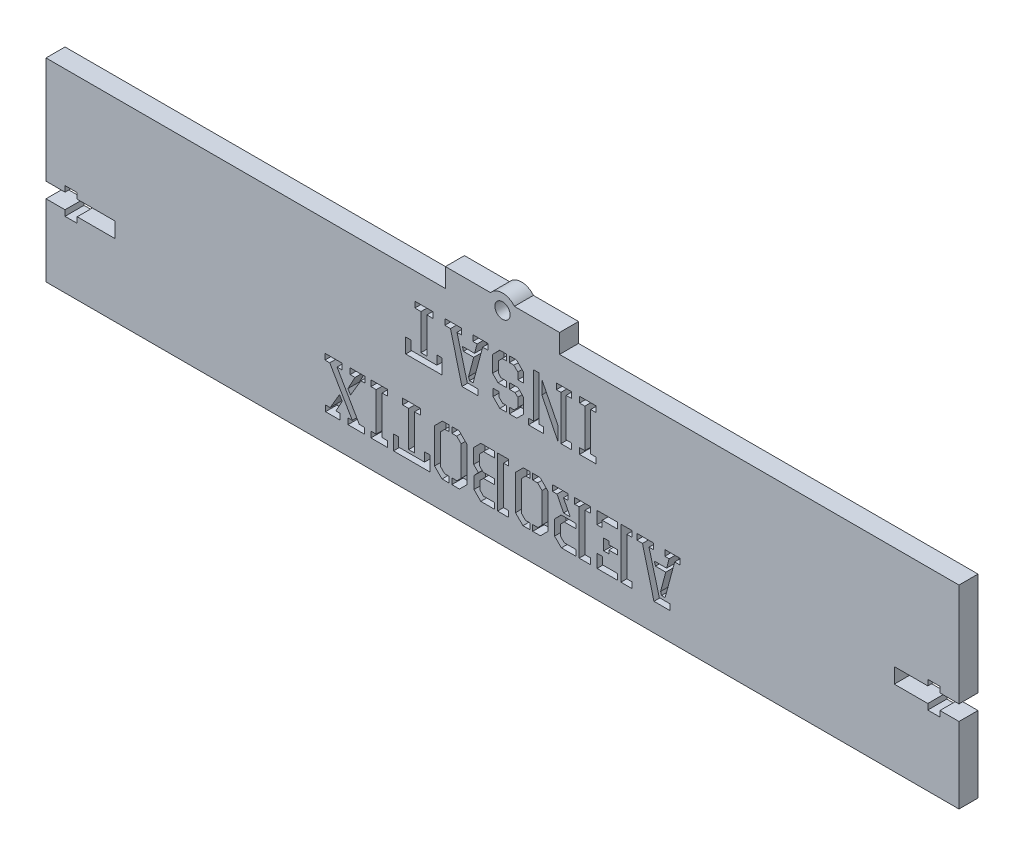
SolidWorks part; units mm, degrees
ref_plane "Front Plane" through (0, 0, 0) normal (0, 0, 1) x (1, 0, 0)
ref_plane "Top Plane" through (0, 0, 0) normal (0, 1, 0) x (1, 0, 0)
ref_plane "Right Plane" through (0, 0, 0) normal (1, 0, 0) x (0, 0, -1)
sketch "Sketch1" plane through (0, 0, 0) normal (0, 0, 1) x (1, 0, 0)
  line L1 (-120, 25.5) -> (120, 25.5)
  line L2 (-120, 25.5) -> (-120, -25.5)
  line L3 (-120, -25.5) -> (120, -25.5)
  line L4 (120, 25.5) -> (120, -25.5)
  dimension "D1" = 240
  dimension "D2" = 51
  dimension "D3" = 25.5
  dimension "D4" = 120
extrude "Boss-Extrude1" add sketch "Sketch1" along normal blind 5
sketch "Sketch4" plane through (0, 0, 5) normal (0, 0, 1) x (1, 0, 0)
  line L0 (120, 25.5) -> (-120, 25.5) construction
  line L1 (-15, 25.5) -> (15, 25.5)
  line L2 (-15, 25.5) -> (-15, 30.5)
  line L3 (-15, 30.5) -> (15, 30.5)
  line L4 (15, 25.5) -> (15, 30.5)
  line L5 (-120, 25.5) -> (-120, -25.5) construction
  dimension "D1" = 105
  dimension "D2" = 30
  dimension "D3" = 5
extrude "Boss-Extrude2" add sketch "Sketch4" against normal blind 5
sketch "Sketch5" plane through (0, 0, 5) normal (0, 0, 1) x (1, 0, 0)
  line L0 (-120, -25.5) -> (120, -25.5) construction
  line L1 (17.5, -25.5) -> (67.5, -25.5)
  line L2 (17.5, -25.5) -> (17.5, -30.5)
  line L3 (17.5, -30.5) -> (67.5, -30.5)
  line L4 (67.5, -25.5) -> (67.5, -30.5)
  line L5 (120, -25.5) -> (120, 25.5) construction
  line L11 (0, 0) -> (0, -46.5213) construction
  line L12 (-67.5, -25.5) -> (-67.5, -30.5)
  line L13 (-17.5, -30.5) -> (-67.5, -30.5)
  line L14 (-17.5, -25.5) -> (-17.5, -30.5)
  line L15 (-17.5, -25.5) -> (-67.5, -25.5)
  point P10 (67.5, -28)
  dimension "D1" = 52.5
  dimension "D2" = 50
  dimension "D3" = 5
extrude "Boss-Extrude3" [suppressed] add sketch "Sketch5" against normal blind 5
sketch "Sketch6" plane through (0, 0, 5) normal (0, 0, 1) x (1, 0, 0)
  line L0 (120, -0.5622) -> (115, -0.5622)
  line L1 (120, -25.5) -> (120, 25.5) construction
  line L2 (105, -0.5622) -> (105, -4.5622)
  line L3 (105, -4.5622) -> (111.8, -4.5622)
  line L4 (120, -4.5622) -> (120, -0.5622)
  line L5 (111.8, -0.5622) -> (111.8, 0.9378)
  line L6 (111.8, 0.9378) -> (115, 0.9378)
  line L7 (115, 0.9378) -> (115, -0.5622)
  line L8 (115, -4.5622) -> (115, -6.0622)
  line L9 (115, -6.0622) -> (111.8, -6.0622)
  line L10 (111.8, -6.0622) -> (111.8, -4.5622)
  line L11 (111.8, -0.5622) -> (105, -0.5622)
  line L12 (115, -4.5622) -> (120, -4.5622)
  line L13 (0, 0) -> (0, -13.303) construction
  line L14 (-115, -4.5622) -> (-120, -4.5622)
  line L15 (-111.8, -0.5622) -> (-105, -0.5622)
  line L16 (-111.8, -6.0622) -> (-111.8, -4.5622)
  line L17 (-115, -6.0622) -> (-111.8, -6.0622)
  line L18 (-115, -4.5622) -> (-115, -6.0622)
  line L19 (-115, 0.9378) -> (-115, -0.5622)
  line L20 (-111.8, 0.9378) -> (-115, 0.9378)
  line L21 (-111.8, -0.5622) -> (-111.8, 0.9378)
  line L22 (-120, -4.5622) -> (-120, -0.5622)
  line L23 (-105, -4.5622) -> (-111.8, -4.5622)
  line L24 (-105, -0.5622) -> (-105, -4.5622)
  line L25 (-120, -0.5622) -> (-115, -0.5622)
  dimension "D1" = 4
  dimension "D2" = 3.2
  dimension "D3" = 15
  dimension "D4" = 5
  dimension "D5" = 1.5
  dimension "D6" = 1.5
extrude "Cut-Extrude1" [suppressed] cut sketch "Sketch6" against normal blind 10
sketch "Sketch7" plane through (0, 0, 5) normal (0, 0, 1) x (1, 0, 0)
  circle A0 centre (0, 28) radius 2
  dimension "D1" = 4
extrude "Cut-Extrude2" cut sketch "Sketch7" against normal blind 5
sketch "Sketch8" plane through (0, 0, 5) normal (0, 0, 1) x (1, 0, 0)
  circle A0 centre (0, 28) radius 2
  circle A1 centre (0, 28) radius 4
  dimension "D1" = 4
  dimension "D2" = 8
extrude "Boss-Extrude4" add sketch "Sketch8" against normal blind 5
sketch "Sketch9" plane through (0, 0, 5) normal (0, 0, 1) x (1, 0, 0)
  line L0 (-72.9229, -5.0597) -> (72.9229, -5.0597) construction
  text T0 "AerobotiX\r\nINSAT" font "Octin Prison Rg" height in points 50
extrude "Cut-Extrude3" cut sketch "Sketch9" against normal blind 3
sketch "Sketch10" plane through (0, 0, 5) normal (0, 0, 1) x (1, 0, 0)
  line L0 (-124, -4.5622) -> (-108.0016, -4.5622) construction
  line L3 (-120, 25.5) -> (-120, -25.5) construction
  line L4 (-120, -6.5622) -> (-115, -6.5622)
  line L5 (-115, -6.5622) -> (-115, -8.0622)
  line L6 (-115, -8.0622) -> (-111.8, -8.0622)
  line L7 (-111.8, -8.0622) -> (-111.8, -6.5622)
  line L8 (-111.8, -6.5622) -> (-101.8, -6.5622)
  line L9 (-101.8, -6.5622) -> (-101.8, -2.5622)
  line L10 (-101.8, -2.5622) -> (-111.8, -2.5622)
  line L11 (-111.8, -2.5622) -> (-111.8, -1.0622)
  line L12 (-111.8, -1.0622) -> (-115, -1.0622)
  line L13 (-115, -1.0622) -> (-115, -2.5622)
  line L14 (-115, -2.5622) -> (-120, -2.5622)
  line L16 (-120, -2.5622) -> (-120, -6.5622)
  line L17 (-120, -25.5) -> (120, -25.5) construction
  line L18 (0, 0) -> (0, -40.5578) construction
  dimension "D1" = 15.9984
  dimension "D2" = 20.9378
  dimension "D3" = 2
  dimension "D4" = 2
  dimension "D5" = 1.5
  dimension "D6" = 1.5
  dimension "D7" = 3.2
  dimension "D8" = 10
  dimension "D9" = 5
extrude "Cut-Extrude4" cut sketch "Sketch10" against normal blind 10
sketch "Sketch12" plane through (0, 0, 5) normal (0, 0, 1) x (1, 0, 0)
  line L0 (120, -1.5622) -> (120, -5.5622)
  line L1 (-120, -25.5) -> (120, -25.5) construction
  line L2 (115.1751, -3.5622) -> (122.5701, -3.5622) construction
  line L3 (120, -25.5) -> (120, 25.5) construction
  line L4 (120, -5.5622) -> (115, -5.5622)
  line L5 (115, -5.5622) -> (115, -7.0622)
  line L6 (115, -7.0622) -> (111.8, -7.0622)
  line L7 (111.8, -7.0622) -> (111.8, -5.5622)
  line L8 (111.8, -5.5622) -> (103, -5.5622)
  line L9 (103, -5.5622) -> (103, -1.5622)
  line L10 (103, -1.5622) -> (111.8, -1.5622)
  line L11 (111.8, -1.5622) -> (111.8, -0.0622)
  line L12 (111.8, -0.0622) -> (115, -0.0622)
  line L13 (115, -0.0622) -> (115, -1.5622)
  line L14 (115, -1.5622) -> (120, -1.5622)
  dimension "D1" = 2
  dimension "D2" = 21.9378
  dimension "D3" = 2
  dimension "D4" = 1.5
  dimension "D5" = 1.5
  dimension "D6" = 3.2
  dimension "D7" = 5
  dimension "D8" = 17
extrude "Cut-Extrude5" cut sketch "Sketch12" against normal blind 10
